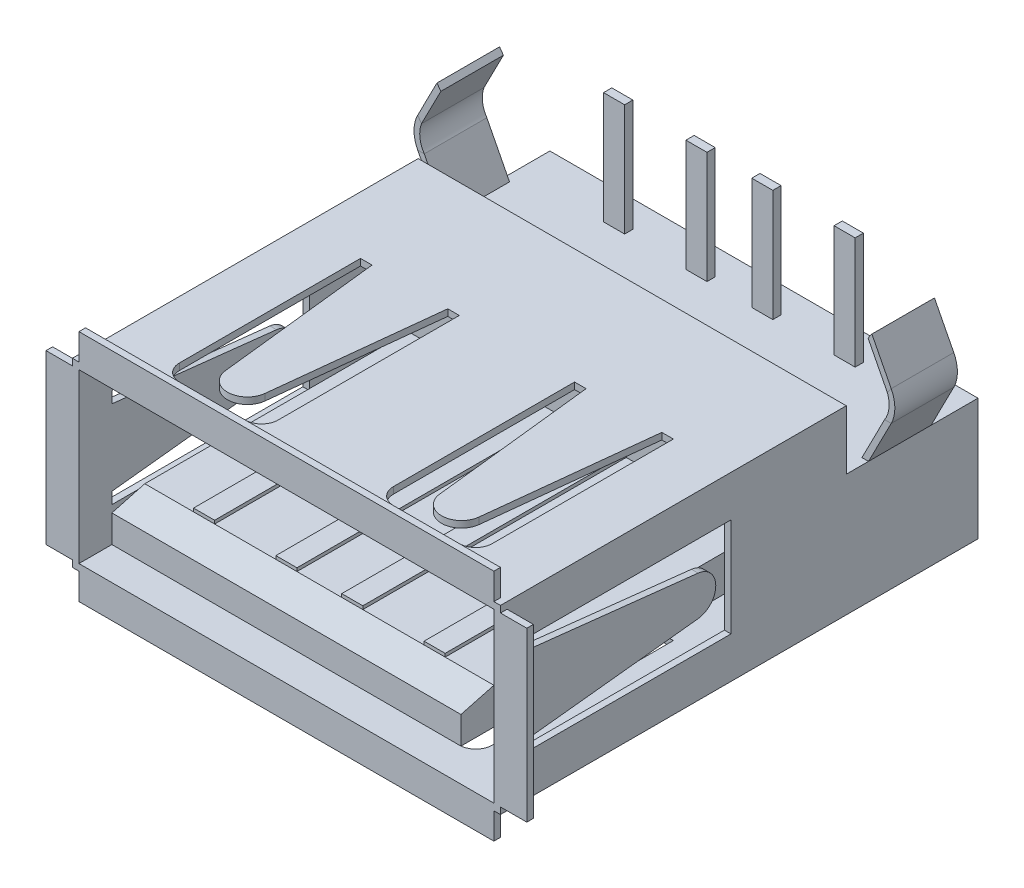
SolidWorks part; units mm, degrees
ref_plane "前视基准面" through (0, 0, 0) normal (0, 0, 1) x (1, 0, 0)
ref_plane "上视基准面" through (0, 0, 0) normal (0, 1, 0) x (1, 0, 0)
ref_plane "右视基准面" through (0, 0, 0) normal (1, 0, 0) x (0, 0, -1)
sketch "草图1" plane through (0, 0, 0) normal (0, 0, 1) x (1, 0, 0)
  line L1 (6.5, -2.75) -> (-6.5, -2.75)
  line L2 (6.5, -2.75) -> (6.5, 2.75)
  line L3 (6.5, 2.75) -> (-6.5, 2.75)
  line L4 (-6.5, -2.75) -> (-6.5, 2.75)
  line L5 (6.5, -2.75) -> (-6.5, 2.75) construction
  line L6 (6.5, 2.75) -> (-6.5, -2.75) construction
  point P0 (0, 0)
  dimension "D1" = 13
  dimension "D2" = 5.5
extrude "凸台-拉伸1" add sketch "草图1" along normal blind 14.5
sketch "草图2" plane through (0, 0, 14.5) normal (0, 0, 1) x (1, 0, 0)
  line L17 (6.3, 2.55) -> (-6.3, 2.55)
  line L18 (6.3, -2.55) -> (6.3, 2.55)
  line L19 (-6.3, -2.55) -> (6.3, -2.55)
  line L20 (-6.3, 2.55) -> (-6.3, -2.55)
  line L21 (6.3, 2.55) -> (-6.3, 2.55)
  line L22 (6.3, -2.55) -> (6.3, 2.55)
  line L23 (-6.3, -2.55) -> (6.3, -2.55)
  line L24 (-6.3, 2.55) -> (-6.3, -2.55)
  dimension "D2" = 0.2
extrude "切除-拉伸1" cut sketch "草图2" against normal blind 9
sketch "草图11" plane through (0, -2.75, 0) normal (0, -1, 0) x (1, 0, 0)
  line L0 (4.75, 7.5) -> (4.75, 13)
  line L1 (4.25, 13.5) -> (2.25, 13.5)
  line L2 (1.75, 13) -> (1.75, 7.5)
  line L3 (4.75, 7.5) -> (4.4, 7.5)
  line L4 (2.1, 7.5) -> (2.65, 12.5)
  line L5 (2.1, 7.5) -> (1.75, 7.5)
  line L6 (3.85, 12.5) -> (4.4, 7.5)
  line L7 (0, 0) -> (0, 15.6851) construction
  line L8 (3.25, 5.9079) -> (3.25, 13.4637) construction
  line L10 (6.5, 14.5) -> (6.5, 0) construction
  line L11 (-3.85, 12.5) -> (-4.4, 7.5)
  line L12 (-2.1, 7.5) -> (-1.75, 7.5)
  line L13 (-2.1, 7.5) -> (-2.65, 12.5)
  line L14 (-4.75, 7.5) -> (-4.4, 7.5)
  line L15 (-1.75, 13) -> (-1.75, 7.5)
  line L16 (-4.25, 13.5) -> (-2.25, 13.5)
  line L17 (-4.75, 7.5) -> (-4.75, 13)
  line L18 (-6.5, 14.5) -> (6.5, 14.5) construction
  arc A0 (1.75, 13) -> (2.25, 13.5) centre (2.25, 13) cw
  arc A1 (4.25, 13.5) -> (4.75, 13) centre (4.25, 13) cw
  arc A2 (2.65, 12.5) -> (3.85, 12.5) centre (3.25, 12.434) cw
  arc A3 (-2.65, 12.5) -> (-3.85, 12.5) centre (-3.25, 12.434) ccw
  arc A4 (-4.25, 13.5) -> (-4.75, 13) centre (-4.25, 13) ccw
  arc A5 (-1.75, 13) -> (-2.25, 13.5) centre (-2.25, 13) ccw
  point P17 (1.75, 13.5)
  point P20 (4.75, 13.5)
  point P35 (-4.75, 13.5)
  point P36 (-1.75, 13.5)
  dimension "D6" = 0.5
  dimension "D1" = 2.3
  dimension "D2" = 3
  dimension "D3" = 6
  dimension "D4" = 1.2
  dimension "D5" = 5
  dimension "D7" = 1
extrude "切除-拉伸3" cut sketch "草图11" against normal through all
sketch "草图12" plane through (6.5, 0, 0) normal (1, 0, 0) x (0, 0, -1)
  line L0 (-13.5, -1.5) -> (-7.5, -1.5)
  line L1 (-7.5, -1.5) -> (-7.5, 1.5)
  line L2 (-7.5, 1.5) -> (-13.5, 1.5)
  line L3 (-13.5, 1.5) -> (-13.5, 1.15)
  line L4 (-13.5, 1.15) -> (-8.5, 0.6)
  line L6 (-8.5, -0.6) -> (-13.5, -1.15)
  line L7 (-13.5, -1.15) -> (-13.5, -1.5)
  line L8 (0, 0) -> (-16.0107, 0) construction
  line L9 (-14.5, -2.75) -> (-14.5, 2.75) construction
  arc A0 (-8.5, -0.6) -> (-8.5, 0.6) centre (-8.566, 0) ccw
  dimension "D1" = 1
  dimension "D2" = 6
  dimension "D3" = 5
  dimension "D4" = 3
  dimension "D5" = 2.3
  dimension "D6" = 1.2
extrude "切除-拉伸4" cut sketch "草图12" against normal through all
sketch "草图5" plane through (0, 0, 5.5) normal (0, 0, 1) x (1, 0, 0)
  line L0 (0, -1.4303) -> (0, 3.5568) construction
  line L1 (5.3, -1.55) -> (-5.3, -1.55)
  line L2 (5.3, -1.55) -> (5.3, -0.45)
  line L3 (5.3, -0.45) -> (-5.3, -0.45)
  line L4 (-5.3, -1.55) -> (-5.3, -0.45)
  line L5 (5.3, -1.55) -> (-5.3, -0.45) construction
  line L6 (5.3, -0.45) -> (-5.3, -1.55) construction
  line L7 (-6.3, 2.55) -> (-6.3, -2.55) construction
  line L8 (-6.3, -2.55) -> (6.3, -2.55) construction
  point P0 (0, -1)
  dimension "D1" = 1.1
  dimension "D2" = 1
  dimension "D3" = 1
extrude "凸台-拉伸3" add sketch "草图5" along normal up to surface (9 mm away) up to face at (0, 0, 14.5)
chamfer "倒角1" distance 1 angle 15 1 edges at (0, -0.45, 14.5)
sketch "草图3" plane through (0, 2.75, 0) normal (0, 1, 0) x (1, 0, 0)
  line L0 (-6.5, -14.5) -> (-6.5, 0) construction
  line L1 (6.5, 0) -> (-6.5, 0)
  line L2 (6.5, 0) -> (6.5, -4)
  line L3 (6.5, -4) -> (-6.5, -4)
  line L4 (-6.5, 0) -> (-6.5, -4)
  dimension "D1" = 4
extrude "切除-拉伸2" cut sketch "草图3" against normal blind 1.8
sketch "草图9" plane through (0, 0.95, 2.45) normal (0, -1, 0) x (-1, 0, 0)
  line L0 (0, 2.45) -> (0, -1.3538) construction
  line L1 (-3.82, 1.65) -> (-3.18, 1.65)
  line L2 (-3.82, 1.65) -> (-3.82, 1.4)
  line L3 (-3.82, 1.4) -> (-3.18, 1.4)
  line L4 (-3.18, 1.65) -> (-3.18, 1.4)
  line L6 (-6.5, 2.45) -> (6.5, 2.45) construction
  line L7 (0.68, 1.4) -> (0.68, 1.65)
  line L8 (-1.32, 1.4) -> (-0.68, 1.4)
  line L9 (-1.32, 1.4) -> (-1.32, 1.65)
  line L10 (-1.32, 1.65) -> (-0.68, 1.65)
  line L11 (-0.68, 1.4) -> (-0.68, 1.65)
  line L12 (1.32, 1.65) -> (0.68, 1.65)
  line L13 (1.32, 1.4) -> (1.32, 1.65)
  line L14 (1.32, 1.4) -> (0.68, 1.4)
  line L15 (3.18, 1.65) -> (3.18, 1.4)
  line L16 (3.82, 1.4) -> (3.18, 1.4)
  line L17 (3.82, 1.65) -> (3.82, 1.4)
  line L18 (3.82, 1.65) -> (3.18, 1.65)
  line L20 (-6.5, -1.55) -> (-6.5, 2.45) construction
  line L21 (-6.5, -0.875) -> (-6.3, -0.875) construction
  line L22 (-6.5, -0.875) -> (-6.5, 1.025) construction
  line L23 (-6.5, 1.025) -> (-6.3, 1.025) construction
  line L24 (-6.3, -0.875) -> (-6.3, 1.025) construction
  point P6 (-1, 1.65)
  point P10 (-3.5, 1.65)
  point P28 (-3.82, 1.525)
  point P29 (-6.3, 0.075)
  dimension "D1" = 0.64
  dimension "D2" = 0.25
  dimension "D3" = 3.5
  dimension "D4" = 1
  dimension "D5" = 0.8
  dimension "D6" = 0.2
  dimension "D7" = 1.9
  dimension "D8" = 1.45
extrude "凸台-拉伸5" add sketch "草图9" against normal blind 3.4
sketch "草图14" plane through (0, -0.45, 0) normal (0, 1, 0) x (1, 0, 0)
  line L1 (-3.82, -5.37) -> (-3.18, -5.37)
  line L2 (-3.82, -5.37) -> (-3.82, -13.5)
  line L3 (-3.82, -13.5) -> (-3.18, -13.5)
  line L4 (-3.18, -5.37) -> (-3.18, -13.5)
  line L5 (-1.32, -5.37) -> (-0.68, -5.37)
  line L6 (-1.32, -5.37) -> (-1.32, -13.5)
  line L7 (-1.32, -13.5) -> (-0.68, -13.5)
  line L8 (-0.68, -5.37) -> (-0.68, -13.5)
  line L9 (0.68, -5.37) -> (1.32, -5.37)
  line L10 (0.68, -5.37) -> (0.68, -13.5)
  line L11 (0.68, -13.5) -> (1.32, -13.5)
  line L12 (1.32, -5.37) -> (1.32, -13.5)
  line L13 (3.18, -5.37) -> (3.82, -5.37)
  line L14 (3.18, -5.37) -> (3.18, -13.5)
  line L15 (3.18, -13.5) -> (3.82, -13.5)
  line L16 (3.82, -5.37) -> (3.82, -13.5)
  line L19 (3.18, -1.05) -> (3.18, -0.8) construction
  line L20 (3.82, -0.8) -> (3.82, -1.05) construction
  line L21 (-5.3, -13.5) -> (5.3, -13.5) construction
  point P19 (0, 0)
extrude "凸台-拉伸6" add sketch "草图14" along normal blind 0.1
sketch "草图15" plane through (0, 0.95, 0) normal (0, 1, 0) x (1, 0, 0)
  line L0 (0, 0) -> (0, -3.8038) construction
  line L5 (-6.3, -3.325) -> (-6.3, -1.425)
  line L6 (-6.5, -1.425) -> (-6.3, -1.425)
  line L7 (-6.5, -3.325) -> (-6.5, -1.425)
  line L8 (-6.5, -3.325) -> (-6.3, -3.325)
sketch "草图16" plane through (0, 0, 0) normal (0, 0, -1) x (-1, 0, 0)
  line L0 (6.5, 0.95) -> (7.1896, 2.2933)
  line L1 (7.1896, 3.2067) -> (6.6027, 4.35)
  line L3 (6.5, 0.95) -> (-6.5, 0.95) construction
  line L5 (6.5, 2.75) -> (-6.5, 2.75) construction
  arc A0 (7.1896, 2.2933) -> (7.1896, 3.2067) centre (6.3, 2.75) ccw
  point P3 (0, 0)
  point P13 (7.4241, 2.75)
  point P14 (7.3, 2.75)
  point P16 (0, 0)
  dimension "D3" = 1
  dimension "D1" = 3.4
  dimension "D2" = 7.3
sweep "扫描1" add profiles "草图15" path "草图16"
mirror "镜向1" about plane through (0, 0, 0) normal (1, 0, 0) of "扫描1"
sketch "草图17" plane through (0, 0, 14.5) normal (0, 0, 1) x (1, 0, 0)
  line L0 (-6.5, -2.75) -> (6.5, -2.75) construction
  line L1 (6.3, -2.75) -> (-6.3, -2.75)
  line L2 (6.3, -3.55) -> (6.3, -2.75)
  line L3 (6.3, -3.55) -> (-6.3, -3.55)
  line L4 (7.3, -2.55) -> (6.5, -2.55)
  line L5 (-6.5, 2.75) -> (-6.5, -2.75) construction
  line L6 (-6.5, -2.55) -> (-7.3, -2.55)
  line L7 (-6.5, -2.55) -> (-6.5, 2.55)
  line L8 (-6.3, -3.55) -> (-6.3, -2.75)
  line L9 (-7.3, -2.55) -> (-7.3, 2.55)
  line L10 (6.5, 2.75) -> (-6.5, 2.75) construction
  line L11 (6.3, 2.75) -> (-6.3, 2.75)
  line L12 (-6.5, 2.55) -> (-7.3, 2.55)
  line L13 (6.3, 3.55) -> (-6.3, 3.55)
  line L14 (-6.3, 2.75) -> (-6.3, 3.55)
  line L15 (6.5, -2.75) -> (6.5, 2.75) construction
  line L16 (6.3, 2.75) -> (6.3, 3.55)
  line L17 (6.5, -2.55) -> (6.5, 2.55)
  line L18 (6.5, 2.55) -> (7.3, 2.55)
  line L19 (7.3, -2.55) -> (7.3, 2.55)
  dimension "D1" = 14.6
  dimension "D2" = 7.1
extrude "卷边-外径14*7.1" add sketch "草图17" against normal blind 0.2
